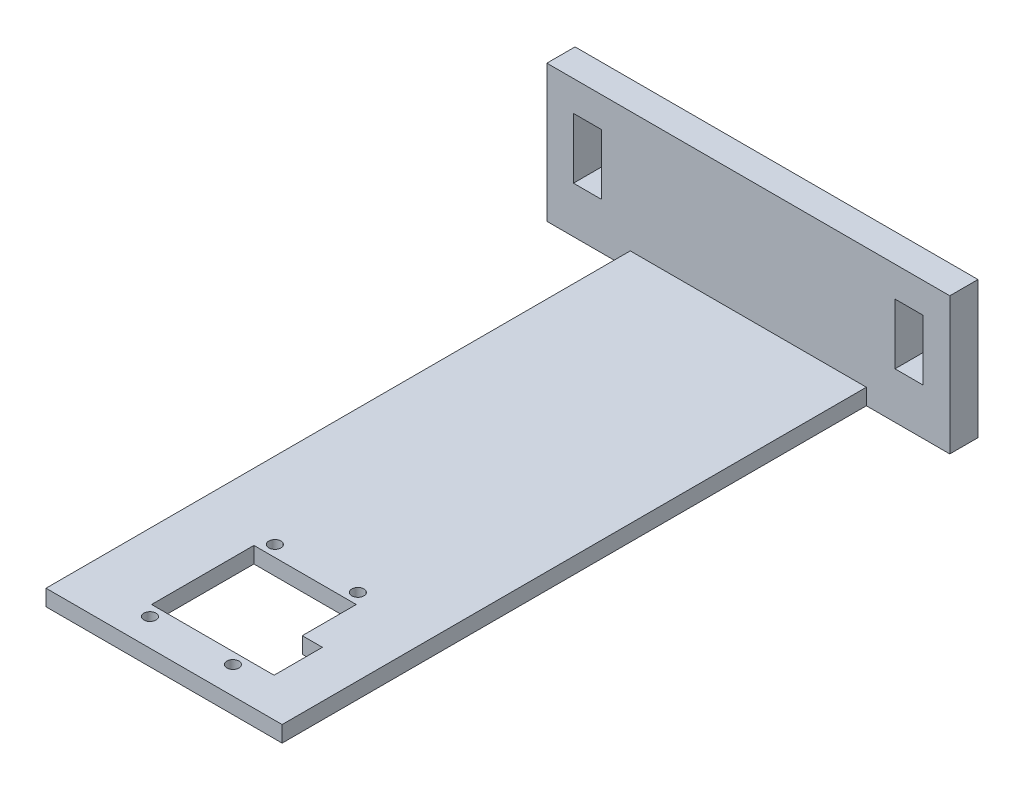
SolidWorks part; units mm, degrees
ref_plane "Front Plane" through (0, 0, 0) normal (0, 0, 1) x (1, 0, 0)
ref_plane "Top Plane" through (0, 0, 0) normal (0, 1, 0) x (1, 0, 0)
ref_plane "Right Plane" through (0, 0, 0) normal (1, 0, 0) x (0, 0, -1)
sketch "Sketch1" plane through (0, 0, 0) normal (0, 1, 0) x (1, 0, 0)
  line L1 (50, -76) -> (-50, -76)
  line L2 (50, -76) -> (50, 76)
  line L3 (50, 76) -> (-50, 76)
  line L4 (-50, -76) -> (-50, 76)
  line L5 (50, -76) -> (-50, 76) construction
  line L6 (50, 76) -> (-50, -76) construction
  point P0 (0, 0)
  dimension "D1" = 100
  dimension "D2" = 152
extrude "Boss-Extrude1" add sketch "Sketch1" along normal blind 34
sketch "Sketch2" plane through (0, 34, 0) normal (0, 1, 0) x (1, 0, 0)
  line L0 (50, -76) -> (50, 76) construction
  line L1 (-50, -76) -> (50, -76)
  line L2 (-50, -76) -> (-50, 69)
  line L3 (-50, 69) -> (50, 69)
  line L4 (50, -76) -> (50, 69)
  line L5 (50, 76) -> (-50, 76) construction
  dimension "D1" = 7
extrude "Cut-Extrude1" cut sketch "Sketch2" against normal blind 30
sketch "Sketch3" plane through (0, 0, -69) normal (0, 0, 1) x (1, 0, 0)
  line L0 (50, 34) -> (-50, 34) construction
  line L1 (-43.4, 26.5) -> (-36.4, 26.5)
  line L2 (-43.4, 26.5) -> (-43.4, 11.5)
  line L3 (-43.4, 11.5) -> (-36.4, 11.5)
  line L4 (-36.4, 26.5) -> (-36.4, 11.5)
  line L5 (36.4, 26.5) -> (43.4, 26.5)
  line L6 (36.4, 26.5) -> (36.4, 11.5)
  line L7 (36.4, 11.5) -> (43.4, 11.5)
  line L8 (43.4, 26.5) -> (43.4, 11.5)
  line L9 (50, 4) -> (-50, 4) construction
  line L10 (-50, 4) -> (-50, 34) construction
  line L11 (50, 4) -> (50, 34) construction
  dimension "D1" = 15
  dimension "D2" = 15
  dimension "D3" = 7.5
  dimension "D4" = 7.5
  dimension "D5" = 7.5
  dimension "D6" = 7.5
  dimension "D7" = 7
  dimension "D8" = 7
  dimension "D9" = 6.6
  dimension "D10" = 6.6
extrude "Cut-Extrude2" cut sketch "Sketch3" against normal through all
sketch "Sketch4" plane through (0, 4, 0) normal (0, 1, 0) x (1, 0, 0)
  line L0 (50, 69) -> (-50, 69) construction
  line L1 (-50, -76) -> (-29.3, -76)
  line L2 (-50, -76) -> (-50, 69)
  line L3 (-50, 69) -> (-29.3, 69)
  line L4 (-29.3, -76) -> (-29.3, 69)
  line L5 (50, 69) -> (-50, 69) construction
  line L6 (50, -76) -> (29.3, -76)
  line L7 (50, -76) -> (50, 69)
  line L8 (50, 69) -> (29.3, 69)
  line L9 (29.3, -76) -> (29.3, 69)
  dimension "D1" = 20.7
  dimension "D2" = 20.7
extrude "Cut-Extrude3" cut sketch "Sketch4" against normal through all
sketch "Sketch5" plane through (0, 4, 0) normal (0, 1, 0) x (1, 0, 0)
  line L0 (-29.3, -76) -> (-29.3, 69) construction
  line L1 (-12.7, -41) -> (12.7, -41)
  line L2 (-12.7, -41) -> (-12.7, -66.4)
  line L3 (-12.7, -66.4) -> (12.7, -66.4)
  line L4 (12.7, -41) -> (12.7, -66.4)
  line L5 (29.3, 69) -> (29.3, -76) construction
  line L6 (-29.3, -76) -> (29.3, -76) construction
  dimension "D1" = 25.4
  dimension "D2" = 25.4
  dimension "D3" = 16.6
  dimension "D4" = 16.6
  dimension "D5" = 35
extrude "Cut-Extrude4" cut sketch "Sketch5" against normal through all
sketch "Sketch7" plane through (0, 4, 0) normal (0, 1, 0) x (1, 0, 0)
  line L0 (12.7, -41) -> (-12.7, -41) construction
  line L1 (-12.7, -66.4) -> (12.7, -66.4) construction
  line L2 (-29.3, -76) -> (-29.3, 69) construction
  line L3 (29.3, 69) -> (29.3, -76) construction
  circle A0 centre (-10.3, -38.2) radius 1.5
  circle A1 centre (10.3, -38.2) radius 1.5
  circle A2 centre (10.3, -69.2) radius 1.5
  circle A3 centre (-10.3, -69.2) radius 1.5
  dimension "D1" = 3
  dimension "D2" = 3
  dimension "D3" = 3
  dimension "D4" = 3
  dimension "D5" = 2.8
  dimension "D6" = 2.8
  dimension "D7" = 2.8
  dimension "D8" = 2.8
  dimension "D9" = 19
  dimension "D10" = 19
  dimension "D11" = 19
  dimension "D12" = 19
  dimension "D13" = 31
extrude "Cut-Extrude5" cut sketch "Sketch7" against normal through all
sketch "Sketch8" plane through (0, 4, 0) normal (0, 1, 0) x (1, 0, 0)
  line L1 (12.7, -66.4) -> (17.7, -66.4)
  line L2 (12.7, -66.4) -> (12.7, -54.4)
  line L3 (12.7, -54.4) -> (17.7, -54.4)
  line L4 (17.7, -66.4) -> (17.7, -54.4)
  dimension "D1" = 5
  dimension "D2" = 12
extrude "Cut-Extrude6" cut sketch "Sketch8" against normal through all
